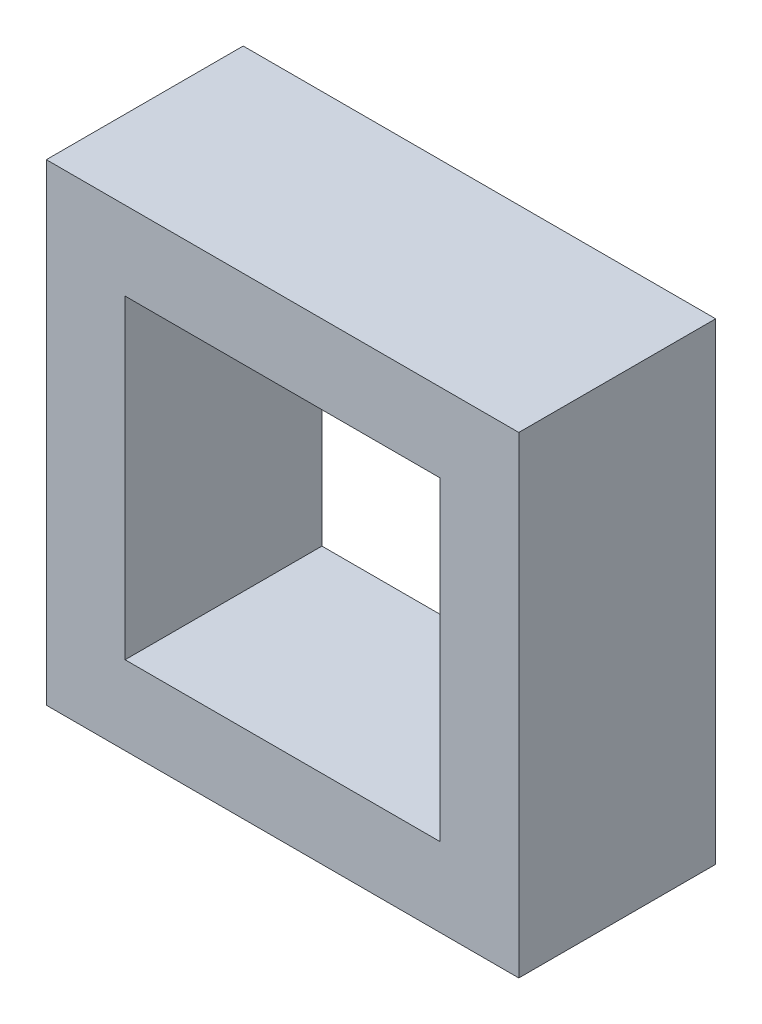
SolidWorks part; units mm, degrees
ref_plane "Top Plane" through (0, 0, 0) normal (0, 0, 1) x (1, 0, 0)
ref_plane "Right Plane" through (0, 0, 0) normal (0, 1, 0) x (1, 0, 0)
ref_plane "Front Plane" through (0, 0, 0) normal (1, 0, 0) x (0, 0, -1)
sketch "Sketch1" plane through (0, 0, 0) normal (0, 0, 1) x (1, 0, 0)
  line L0 (-12, 12) -> (12, -12) construction
  line L1 (-12, 12) -> (12, 12)
  line L2 (-12, 12) -> (-12, -12)
  line L3 (-12, -12) -> (12, -12)
  line L4 (12, 12) -> (12, -12)
  line L5 (-8, 8) -> (8, 8)
  line L6 (8, 8) -> (8, -8)
  line L7 (-8, -8) -> (8, -8)
  line L8 (-8, 8) -> (-8, -8)
  point P4 (0, 0)
  dimension "D1" = 24
  dimension "D2" = 24
  dimension "D3" = 4
extrude "Boss-Extrude1" add sketch "Sketch1" along normal mid plane 10
